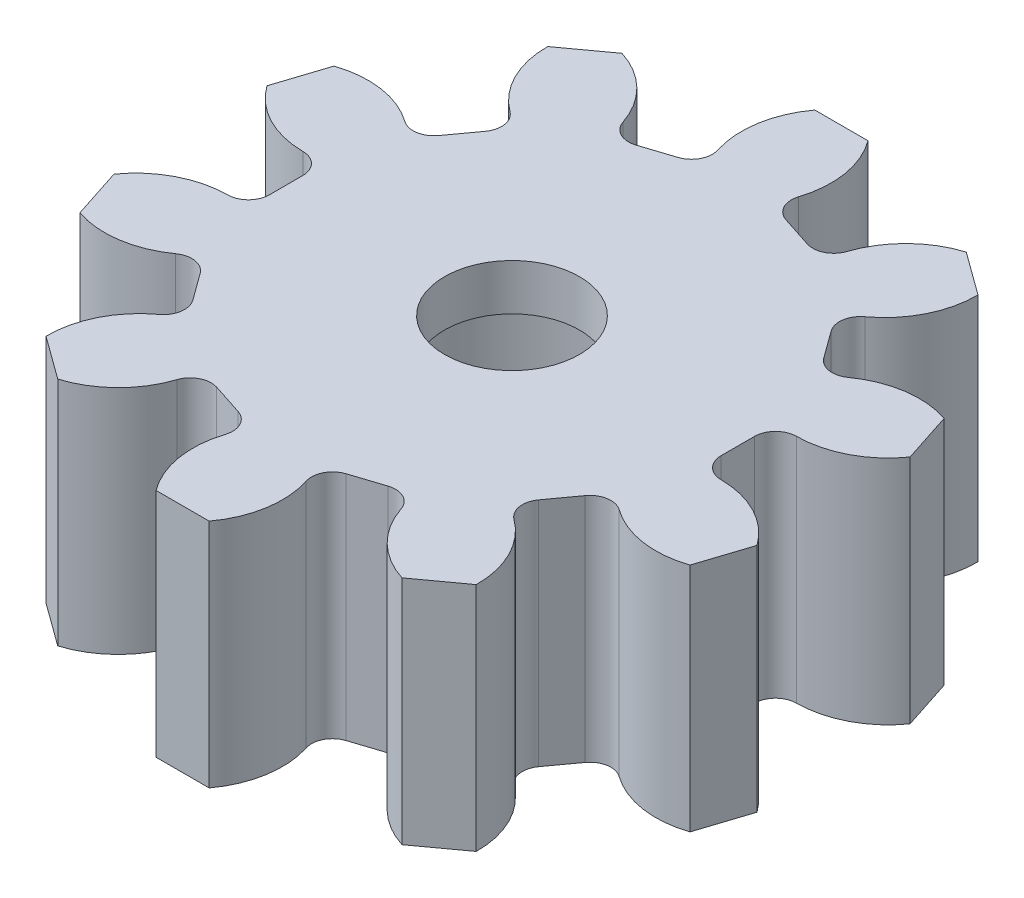
SolidWorks part; units mm, degrees
ref_plane "Front Plane" through (0, 0, 0) normal (0, 0, 1) x (1, 0, 0)
ref_plane "Top Plane" through (0, 0, 0) normal (0, 1, 0) x (1, 0, 0)
ref_plane "Right Plane" through (0, 0, 0) normal (1, 0, 0) x (0, 0, -1)
sketch "Sketch1" plane through (0, 0, 0) normal (0, 1, 0) x (1, 0, 0)
  line L0 (0, 7.1268) -> (0, 4.9) construction
  line L1 (-0.575, 7.1268) -> (0, 7.1268)
  line L2 (0.575, 7.1268) -> (0, 7.1268)
  line L3 (-1.1676, 4.7589) -> (-1.8526, 4.5363)
  line L43 (3.7239, 6.1037) -> (4.1891, 5.7657)
  line L44 (4.6542, 5.4278) -> (4.1891, 5.7657)
  line L45 (1.8526, 4.5363) -> (1.1676, 4.7589)
  line L46 (4.1891, 5.7657) -> (2.8801, 3.9642) construction
  line L47 (6.6003, 2.7492) -> (6.778, 2.2023)
  line L48 (6.9557, 1.6555) -> (6.778, 2.2023)
  line L49 (4.1652, 2.581) -> (3.7418, 3.1637)
  line L50 (6.778, 2.2023) -> (4.6602, 1.5142) construction
  line L51 (6.9557, -1.6555) -> (6.778, -2.2023)
  line L52 (6.6003, -2.7492) -> (6.778, -2.2023)
  line L53 (4.8867, -0.3602) -> (4.8867, 0.3602)
  line L54 (6.778, -2.2023) -> (4.6602, -1.5142) construction
  line L55 (4.6542, -5.4278) -> (4.1891, -5.7657)
  line L56 (3.7239, -6.1037) -> (4.1891, -5.7657)
  line L57 (3.7418, -3.1637) -> (4.1652, -2.581)
  line L58 (4.1891, -5.7657) -> (2.8801, -3.9642) construction
  line L59 (0.575, -7.1268) -> (0, -7.1268)
  line L60 (-0.575, -7.1268) -> (0, -7.1268)
  line L61 (1.1676, -4.7589) -> (1.8526, -4.5363)
  line L62 (0, -7.1268) -> (0, -4.9) construction
  line L63 (-3.7239, -6.1037) -> (-4.1891, -5.7657)
  line L64 (-4.6542, -5.4278) -> (-4.1891, -5.7657)
  line L65 (-1.8526, -4.5363) -> (-1.1676, -4.7589)
  line L66 (-4.1891, -5.7657) -> (-2.8801, -3.9642) construction
  line L67 (-6.6003, -2.7492) -> (-6.778, -2.2023)
  line L68 (-6.9557, -1.6555) -> (-6.778, -2.2023)
  line L69 (-4.1652, -2.581) -> (-3.7418, -3.1637)
  line L70 (-6.778, -2.2023) -> (-4.6602, -1.5142) construction
  line L71 (-6.9557, 1.6555) -> (-6.778, 2.2023)
  line L72 (-6.6003, 2.7492) -> (-6.778, 2.2023)
  line L73 (-4.8867, 0.3602) -> (-4.8867, -0.3602)
  line L74 (-6.778, 2.2023) -> (-4.6602, 1.5142) construction
  line L75 (-4.6542, 5.4278) -> (-4.1891, 5.7657)
  line L76 (-3.7239, 6.1037) -> (-4.1891, 5.7657)
  line L77 (-3.7418, 3.1637) -> (-4.1652, 2.581)
  line L78 (-4.1891, 5.7657) -> (-2.8801, 3.9642) construction
  circle A1 centre (0, 0) radius 6 construction
  circle A2 centre (0, 0) radius 5.4 construction
  circle A3 centre (0, 0) radius 7.15 construction
  arc A4 (-0.575, 7.1268) -> (-0.875, 5.3286) centre (1.0309, 5.9348) ccw
  circle A5 centre (0, 0) radius 4.9 construction
  arc A6 (-0.875, 5.3286) -> (-1.1676, 4.7589) centre (-1.3079, 5.1909) cw
  arc A7 (0.875, 5.3286) -> (1.1676, 4.7589) centre (1.3079, 5.1909) ccw
  arc A8 (0.575, 7.1268) -> (0.875, 5.3286) centre (-1.0309, 5.9348) cw
  arc A61 (3.7239, 6.1037) -> (2.4242, 4.8253) centre (4.3224, 4.1954) ccw
  arc A62 (2.4242, 4.8253) -> (1.8526, 4.5363) centre (1.993, 4.9684) cw
  arc A63 (3.84, 3.7966) -> (3.7418, 3.1637) centre (4.1093, 3.4308) ccw
  arc A64 (4.6542, 5.4278) -> (3.84, 3.7966) centre (2.6543, 5.4073) cw
  arc A65 (6.6003, 2.7492) -> (4.7974, 2.4788) centre (5.9629, 0.8535) ccw
  arc A66 (4.7974, 2.4788) -> (4.1652, 2.581) centre (4.5327, 2.848) cw
  arc A67 (5.3382, 0.8145) -> (4.8867, 0.3602) centre (5.3411, 0.3602) ccw
  arc A68 (6.9557, 1.6555) -> (5.3382, 0.8145) centre (5.3257, 2.8144) cw
  arc A69 (6.9557, -1.6555) -> (5.3382, -0.8145) centre (5.3257, -2.8144) ccw
  arc A70 (5.3382, -0.8145) -> (4.8867, -0.3602) centre (5.3411, -0.3602) cw
  arc A71 (4.7974, -2.4788) -> (4.1652, -2.581) centre (4.5327, -2.848) ccw
  arc A72 (6.6003, -2.7492) -> (4.7974, -2.4788) centre (5.9629, -0.8535) cw
  arc A73 (4.6542, -5.4278) -> (3.84, -3.7966) centre (2.6543, -5.4073) ccw
  arc A74 (3.84, -3.7966) -> (3.7418, -3.1637) centre (4.1093, -3.4308) cw
  arc A75 (2.4242, -4.8253) -> (1.8526, -4.5363) centre (1.993, -4.9684) ccw
  arc A76 (3.7239, -6.1037) -> (2.4242, -4.8253) centre (4.3224, -4.1954) cw
  arc A77 (0.575, -7.1268) -> (0.875, -5.3286) centre (-1.0309, -5.9348) ccw
  arc A78 (0.875, -5.3286) -> (1.1676, -4.7589) centre (1.3079, -5.1909) cw
  arc A79 (-0.875, -5.3286) -> (-1.1676, -4.7589) centre (-1.3079, -5.1909) ccw
  arc A80 (-0.575, -7.1268) -> (-0.875, -5.3286) centre (1.0309, -5.9348) cw
  arc A81 (-3.7239, -6.1037) -> (-2.4242, -4.8253) centre (-4.3224, -4.1954) ccw
  arc A82 (-2.4242, -4.8253) -> (-1.8526, -4.5363) centre (-1.993, -4.9684) cw
  arc A83 (-3.84, -3.7966) -> (-3.7418, -3.1637) centre (-4.1093, -3.4308) ccw
  arc A84 (-4.6542, -5.4278) -> (-3.84, -3.7966) centre (-2.6543, -5.4073) cw
  arc A85 (-6.6003, -2.7492) -> (-4.7974, -2.4788) centre (-5.9629, -0.8535) ccw
  arc A86 (-4.7974, -2.4788) -> (-4.1652, -2.581) centre (-4.5327, -2.848) cw
  arc A87 (-5.3382, -0.8145) -> (-4.8867, -0.3602) centre (-5.3411, -0.3602) ccw
  arc A88 (-6.9557, -1.6555) -> (-5.3382, -0.8145) centre (-5.3257, -2.8144) cw
  arc A89 (-6.9557, 1.6555) -> (-5.3382, 0.8145) centre (-5.3257, 2.8144) ccw
  arc A90 (-5.3382, 0.8145) -> (-4.8867, 0.3602) centre (-5.3411, 0.3602) cw
  arc A91 (-4.7974, 2.4788) -> (-4.1652, 2.581) centre (-4.5327, 2.848) ccw
  arc A92 (-6.6003, 2.7492) -> (-4.7974, 2.4788) centre (-5.9629, 0.8535) cw
  arc A93 (-4.6542, 5.4278) -> (-3.84, 3.7966) centre (-2.6543, 5.4073) ccw
  arc A94 (-3.84, 3.7966) -> (-3.7418, 3.1637) centre (-4.1093, 3.4308) cw
  arc A95 (-2.4242, 4.8253) -> (-1.8526, 4.5363) centre (-1.993, 4.9684) ccw
  arc A96 (-3.7239, 6.1037) -> (-2.4242, 4.8253) centre (-4.3224, 4.1954) cw
  circle A97 centre (0, 0) radius 2.8625
  point P24 (-3.7879, 3.1084)
  dimension "D1" = 1.15
  dimension "D3" = 0.5
  dimension "D4" = 0.6
  dimension "D5" = 14.3
  dimension "D9" = 12
  dimension "D6" = 2
  dimension "D10" = 5.725
  dimension "D7" = 1.75
  dimension "D2" = 10
extrude "Boss-Extrude1" add sketch "Sketch1" along normal blind 5
ref_plane "Plane1" through (0, 4, 0) normal (0, 1, 0) x (1, 0, 0)
sketch "Sketch2" plane through (0, 4, 0) normal (0, 1, 0) x (1, 0, 0)
  circle A1 centre (0, 0) radius 2.8625
  circle A2 centre (0, 0) radius 1.46
  circle A3 centre (0, 0) radius 2.8625 construction
  point P1 (-0.4924, -0.4058)
  point P4 (0, 0)
  dimension "D1" = 2.92
extrude "Boss-Extrude2" add sketch "Sketch2" along normal up to surface (1 mm away) up to face at (0, 5, 0)
